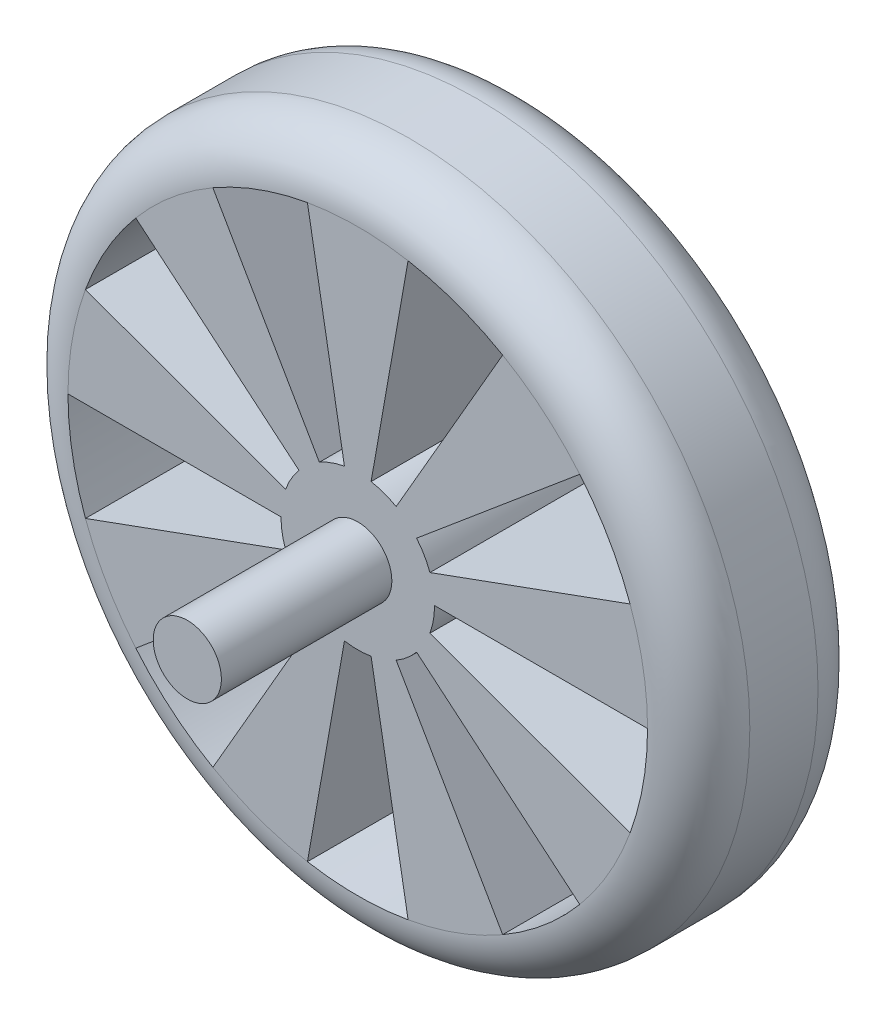
SolidWorks part; units mm, degrees
ref_plane "前视基准面" through (0, 0, 0) normal (0, 0, 1) x (1, 0, 0)
ref_plane "上视基准面" through (0, 0, 0) normal (0, 1, 0) x (1, 0, 0)
ref_plane "右视基准面" through (0, 0, 0) normal (1, 0, 0) x (0, 0, -1)
other "Configuration Table"
sketch "草图1" plane through (0, 0, 0) normal (0, 0, 1) x (1, 0, 0)
  circle A0 centre (0, 0) radius 100
extrude "凸台-拉伸1" add sketch "草图1" along normal blind 50
sketch "草图2" plane through (0, 0, 50) normal (0, 0, 1) x (1, 0, 0)
  circle A0 centre (0, 0) radius 10
extrude "凸台-拉伸2" add sketch "草图2" along normal blind 50
fillet "圆角1" radius 15 2 edges at (100, 0, 0) (100, 0, 50)
sketch "草图3" plane through (0, 0, 50) normal (0, 0, 1) x (1, 0, 0)
  line L0 (0, 0) -> (-14.7601, 83.7087)
  line L1 (0, 0) -> (14.7601, 83.7087)
  line L2 (0, 0) -> (42.5, 73.6122)
  line L3 (0, 0) -> (65.1138, 54.6369)
  line L4 (0, 0) -> (79.8739, 29.0717)
  line L5 (0, 0) -> (85, 0)
  line L6 (0, 0) -> (79.8739, -29.0717)
  line L7 (0, 0) -> (65.1138, -54.6369)
  line L8 (0, 0) -> (42.5, -73.6122)
  line L9 (0, 0) -> (14.7601, -83.7087)
  line L10 (0, 0) -> (-14.7601, -83.7087)
  line L11 (0, 0) -> (-42.5, -73.6122)
  line L12 (0, 0) -> (-65.1138, -54.6369)
  line L13 (0, 0) -> (-79.8739, -29.0717)
  line L14 (0, 0) -> (-85, 0)
  line L15 (0, 0) -> (-79.8739, 29.0717)
  line L16 (0, 0) -> (-65.1138, 54.6369)
  line L17 (0, 0) -> (-42.5, 73.6122)
  line L18 (0, 0) -> (-14.7601, 83.7087) construction
  line L19 (0, 0) -> (14.7601, 83.7087) construction
  circle A0 centre (0, 0) radius 85
  circle A1 centre (0, 0) radius 22.5253
  dimension "D2" = 20
  dimension "D1" = 18
extrude "切除-拉伸1" cut sketch "草图3" against normal through all contours A1 L0 L1 L17 | A1 L2 L1 | A1 L4 L1 L3 | A1 L6 L1 L5 | A1 L8 L1 L7 | A1 L10 L1 L9 | A1 L12 L1 L11 | A1 L14 L1 L13 | A1 L16 L1 L15
